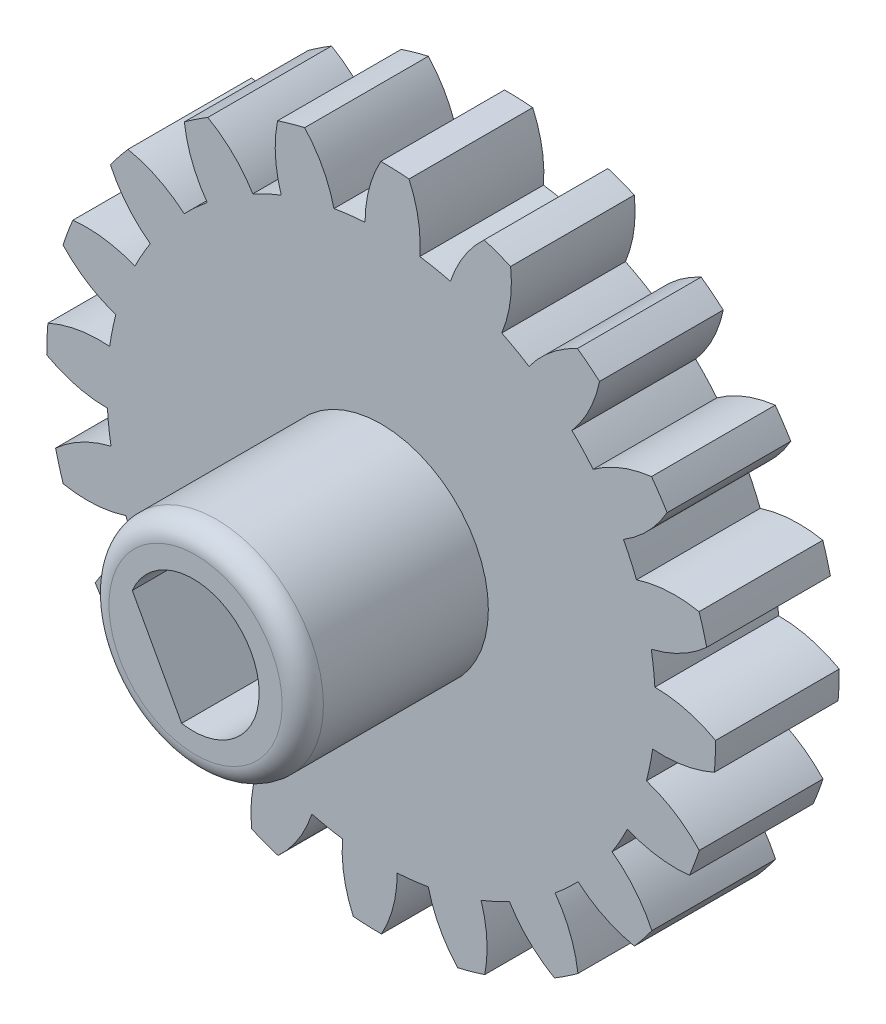
SolidWorks part; units mm, degrees
ref_plane "前视基准面" through (0, 0, 0) normal (0, 0, 1) x (1, 0, 0)
ref_plane "上视基准面" through (0, 0, 0) normal (0, 1, 0) x (1, 0, 0)
ref_plane "右视基准面" through (0, 0, 0) normal (1, 0, 0) x (0, 0, -1)
sketch "草图4" plane through (0, 0, 0) normal (0, 0, 1) x (1, 0, 0)
  arc A0 (6.6376, 0.3903) -> (6.5499, 1.1439) centre (0, 0) ccw
  arc A1 (8.3587, -0.1477) -> (6.6376, 0.3903) centre (6.6319, -2.6497) ccw
  arc A2 (8.3424, -0.5418) -> (8.3587, -0.1477) centre (0, 0) ccw
  arc A3 (6.5828, -0.9361) -> (8.3424, -0.5418) centre (6.8278, 2.094) ccw
  arc A4 (6.4333, -1.6799) -> (6.5828, -0.9361) centre (0, 0) ccw
  arc A5 (7.9039, -2.7235) -> (6.4333, -1.6799) centre (5.4885, -4.5694) ccw
  arc A6 (7.7667, -3.0933) -> (7.9039, -2.7235) centre (0, 0) ccw
  arc A7 (5.9714, -2.9245) -> (7.7667, -3.0933) centre (7.1407, -0.1184) ccw
  arc A8 (5.5993, -3.5857) -> (5.9714, -2.9245) centre (0, 0) ccw
  arc A9 (6.6755, -5.0326) -> (5.5993, -3.5857) centre (3.8079, -6.0418) ccw
  arc A10 (6.4307, -5.3419) -> (6.6755, -5.0326) centre (0, 0) ccw
  arc A11 (4.7754, -4.6266) -> (6.4307, -5.3419) centre (6.7546, -2.3192) ccw
  arc A12 (4.2172, -5.1405) -> (4.7754, -4.6266) centre (0, 0) ccw
  arc A13 (4.7936, -6.8492) -> (4.2172, -5.1405) centre (1.7545, -6.9228) ccw
  arc A14 (4.4652, -7.0676) -> (4.7936, -6.8492) centre (0, 0) ccw
  arc A15 (3.1119, -5.8759) -> (4.4652, -7.0676) centre (5.7073, -4.293) ccw
  arc A16 (2.4223, -6.1921) -> (3.1119, -5.8759) centre (0, 0) ccw
  arc A17 (2.4425, -7.9952) -> (2.4223, -6.1921) centre (-0.4706, -7.1261) ccw
  arc A18 (2.0626, -8.1015) -> (2.4425, -7.9952) centre (0, 0) ccw
  arc A19 (1.1439, -6.5499) -> (2.0626, -8.1015) centre (4.1014, -5.8465) ccw
  arc A20 (0.3903, -6.6376) -> (1.1439, -6.5499) centre (0, 0) ccw
  arc A21 (-0.1477, -8.3587) -> (0.3903, -6.6376) centre (-2.6497, -6.6319) ccw
  arc A22 (-0.5418, -8.3424) -> (-0.1477, -8.3587) centre (0, 0) ccw
  arc A23 (-0.9361, -6.5828) -> (-0.5418, -8.3424) centre (2.094, -6.8278) ccw
  arc A24 (-1.6799, -6.4333) -> (-0.9361, -6.5828) centre (0, 0) ccw
  arc A25 (-2.7235, -7.9039) -> (-1.6799, -6.4333) centre (-4.5694, -5.4885) ccw
  arc A26 (-3.0933, -7.7667) -> (-2.7235, -7.9039) centre (0, 0) ccw
  arc A27 (-2.9245, -5.9714) -> (-3.0933, -7.7667) centre (-0.1184, -7.1407) ccw
  arc A28 (-3.5857, -5.5993) -> (-2.9245, -5.9714) centre (0, 0) ccw
  arc A29 (-5.0326, -6.6755) -> (-3.5857, -5.5993) centre (-6.0418, -3.8079) ccw
  arc A30 (-5.3419, -6.4307) -> (-5.0326, -6.6755) centre (0, 0) ccw
  arc A31 (-4.6266, -4.7754) -> (-5.3419, -6.4307) centre (-2.3192, -6.7546) ccw
  arc A32 (-5.1405, -4.2172) -> (-4.6266, -4.7754) centre (0, 0) ccw
  arc A33 (-6.8492, -4.7936) -> (-5.1405, -4.2172) centre (-6.9228, -1.7545) ccw
  arc A34 (-7.0676, -4.4652) -> (-6.8492, -4.7936) centre (0, 0) ccw
  arc A35 (-5.8759, -3.1119) -> (-7.0676, -4.4652) centre (-4.293, -5.7073) ccw
  arc A36 (-6.1921, -2.4223) -> (-5.8759, -3.1119) centre (0, 0) ccw
  arc A37 (-7.9952, -2.4425) -> (-6.1921, -2.4223) centre (-7.1261, 0.4706) ccw
  arc A38 (-8.1015, -2.0626) -> (-7.9952, -2.4425) centre (0, 0) ccw
  arc A39 (-6.5499, -1.1439) -> (-8.1015, -2.0626) centre (-5.8465, -4.1014) ccw
  arc A40 (-6.6376, -0.3903) -> (-6.5499, -1.1439) centre (0, 0) ccw
  arc A41 (-8.3587, 0.1477) -> (-6.6376, -0.3903) centre (-6.6319, 2.6497) ccw
  arc A42 (-8.3424, 0.5418) -> (-8.3587, 0.1477) centre (0, 0) ccw
  arc A43 (-6.5828, 0.9361) -> (-8.3424, 0.5418) centre (-6.8278, -2.094) ccw
  arc A44 (-6.4333, 1.6799) -> (-6.5828, 0.9361) centre (0, 0) ccw
  arc A45 (-7.9039, 2.7235) -> (-6.4333, 1.6799) centre (-5.4885, 4.5694) ccw
  arc A46 (-7.7667, 3.0933) -> (-7.9039, 2.7235) centre (0, 0) ccw
  arc A47 (-5.9714, 2.9245) -> (-7.7667, 3.0933) centre (-7.1407, 0.1184) ccw
  arc A48 (-5.5993, 3.5857) -> (-5.9714, 2.9245) centre (0, 0) ccw
  arc A49 (-6.6755, 5.0326) -> (-5.5993, 3.5857) centre (-3.8079, 6.0418) ccw
  arc A50 (-6.4307, 5.3419) -> (-6.6755, 5.0326) centre (0, 0) ccw
  arc A51 (-4.7754, 4.6266) -> (-6.4307, 5.3419) centre (-6.7546, 2.3192) ccw
  arc A52 (-4.2172, 5.1405) -> (-4.7754, 4.6266) centre (0, 0) ccw
  arc A53 (-4.7936, 6.8492) -> (-4.2172, 5.1405) centre (-1.7545, 6.9228) ccw
  arc A54 (-4.4652, 7.0676) -> (-4.7936, 6.8492) centre (0, 0) ccw
  arc A55 (-3.1119, 5.8759) -> (-4.4652, 7.0676) centre (-5.7073, 4.293) ccw
  arc A56 (-2.4223, 6.1921) -> (-3.1119, 5.8759) centre (0, 0) ccw
  arc A57 (-2.4425, 7.9952) -> (-2.4223, 6.1921) centre (0.4706, 7.1261) ccw
  arc A58 (-2.0626, 8.1015) -> (-2.4425, 7.9952) centre (0, 0) ccw
  arc A59 (-1.1439, 6.5499) -> (-2.0626, 8.1015) centre (-4.1014, 5.8465) ccw
  arc A60 (-0.3903, 6.6376) -> (-1.1439, 6.5499) centre (0, 0) ccw
  arc A61 (0.1477, 8.3587) -> (-0.3903, 6.6376) centre (2.6497, 6.6319) ccw
  arc A62 (0.5418, 8.3424) -> (0.1477, 8.3587) centre (0, 0) ccw
  arc A63 (0.9361, 6.5828) -> (0.5418, 8.3424) centre (-2.094, 6.8278) ccw
  arc A64 (1.6799, 6.4333) -> (0.9361, 6.5828) centre (0, 0) ccw
  arc A65 (2.7235, 7.9039) -> (1.6799, 6.4333) centre (4.5694, 5.4885) ccw
  arc A66 (3.0933, 7.7667) -> (2.7235, 7.9039) centre (0, 0) ccw
  arc A67 (2.9245, 5.9714) -> (3.0933, 7.7667) centre (0.1184, 7.1407) ccw
  arc A68 (3.5857, 5.5993) -> (2.9245, 5.9714) centre (0, 0) ccw
  arc A69 (5.0326, 6.6755) -> (3.5857, 5.5993) centre (6.0418, 3.8079) ccw
  arc A70 (5.3419, 6.4307) -> (5.0326, 6.6755) centre (0, 0) ccw
  arc A71 (4.6266, 4.7754) -> (5.3419, 6.4307) centre (2.3192, 6.7546) ccw
  arc A72 (5.1405, 4.2172) -> (4.6266, 4.7754) centre (0, 0) ccw
  arc A73 (6.8492, 4.7936) -> (5.1405, 4.2172) centre (6.9228, 1.7545) ccw
  arc A74 (7.0676, 4.4652) -> (6.8492, 4.7936) centre (0, 0) ccw
  arc A75 (5.8759, 3.1119) -> (7.0676, 4.4652) centre (4.293, 5.7073) ccw
  arc A76 (6.1921, 2.4223) -> (5.8759, 3.1119) centre (0, 0) ccw
  arc A77 (7.9952, 2.4425) -> (6.1921, 2.4223) centre (7.1261, -0.4706) ccw
  arc A78 (8.1015, 2.0626) -> (7.9952, 2.4425) centre (0, 0) ccw
  arc A79 (6.5499, 1.1439) -> (8.1015, 2.0626) centre (5.8465, 4.1014) ccw
  circle A81 centre (0, 0) radius 8.1093
extrude "凸台-拉伸4" add sketch "草图4" along normal blind 3 contours A79 A81 A77 A76 A75 A73 A72 A71 A69 A68 A67 A65 A64 A63 A61 A60 A59 A57 A56 A55 A53 A52 A51 A49 A48 A47 A45 A44 A43 A41 A40 A39 A37 A36 A35 A33 A32 A31 A29
sketch "草图5" plane through (0, 0, 3) normal (0, 0, 1) x (1, 0, 0)
  circle A0 centre (0, 0) radius 2.6
extrude "凸台-拉伸6" add sketch "草图5" along normal blind 4.5
fillet "圆角1" radius 0.5 1 edges at (2.6, 0, 7.5)
sketch "草图8" plane through (0, 0, 0) normal (0, 0, -1) x (-1, 0, 0)
  line L1 (0.3383, -1.6073) -> (1.5345, 0.5856)
  arc A1 (1.5345, 0.5856) -> (0.3383, -1.6073) centre (0.0585, -0.0319) ccw
  dimension "D1" = 1.6
  dimension "D2" = 1
extrude "切除-拉伸1" cut sketch "草图8" against normal through all
